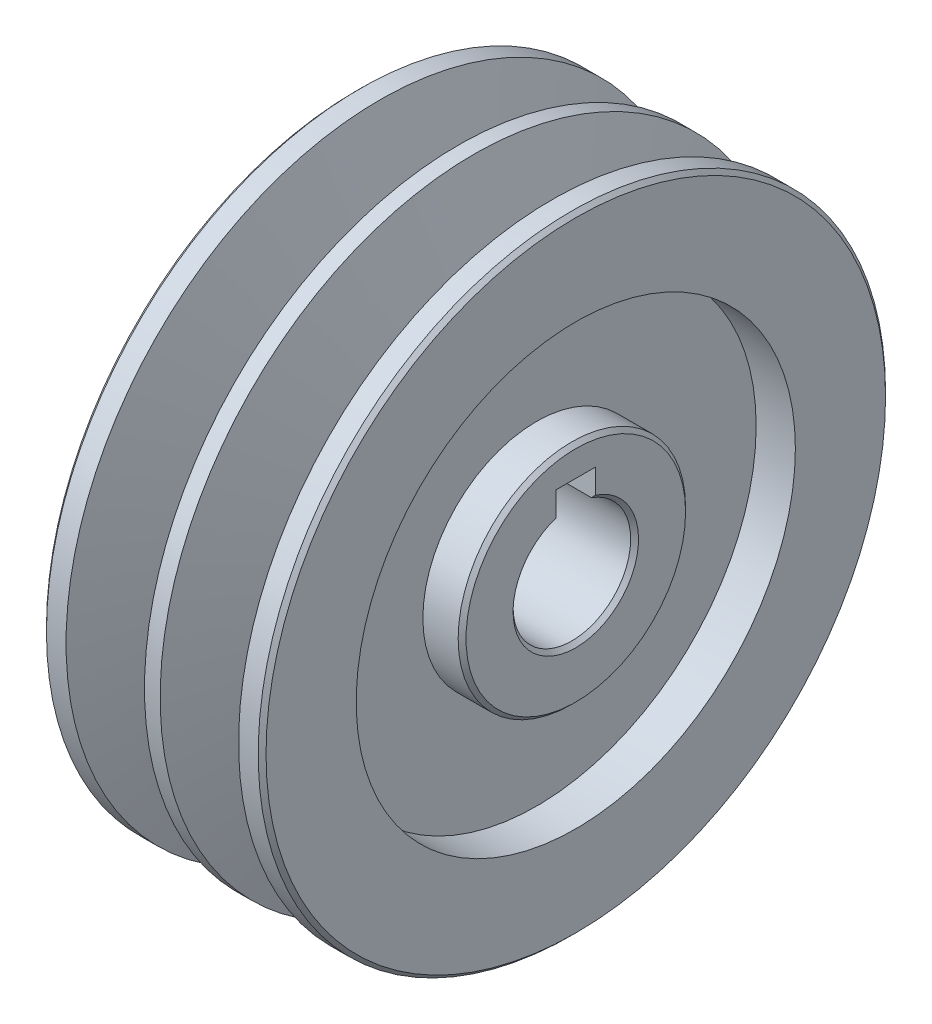
SolidWorks part; units mm, degrees
ref_plane "Front Plane" through (0, 0, 0) normal (0, 0, 1) x (1, 0, 0)
ref_plane "Top Plane" through (0, 0, 0) normal (0, 1, 0) x (1, 0, 0)
ref_plane "Right Plane" through (0, 0, 0) normal (1, 0, 0) x (0, 0, -1)
sketch "Sketch1" plane through (0, 0, 0) normal (0, 1, 0) x (1, 0, 0)
  line L0 (-14, 40) -> (-14, 28)
  line L1 (-14, 40) -> (-11, 40)
  line L2 (14, 40) -> (14, 28)
  line L3 (14, 28) -> (9, 28)
  line L4 (9, 28) -> (9, 14.5)
  line L5 (9, 14.5) -> (14, 14.5)
  line L6 (14, 14.5) -> (14, 7.5)
  line L7 (14, 7.5) -> (-14, 7.5)
  line L8 (-14, 7.5) -> (-14, 14.5)
  line L9 (-14, 14.5) -> (-9, 14.5)
  line L10 (-9, 14.5) -> (-9, 28)
  line L11 (-9, 28) -> (-14, 28)
  line L12 (0, 0) -> (0, 95.8906) construction
  line L13 (1, 40) -> (4.0573, 30)
  line L14 (4.0573, 30) -> (7.9427, 30)
  line L15 (7.9427, 30) -> (11, 40)
  line L16 (11, 40) -> (14, 40)
  line L17 (0, 0) -> (-42.3045, 0) construction
  line L18 (-11, 40) -> (-7.9427, 30)
  line L19 (-7.9427, 30) -> (-4.0573, 30)
  line L20 (-4.0573, 30) -> (-1, 40)
  line L21 (-1, 40) -> (1, 40)
  dimension "D1" = 10
  dimension "D2" = 10
  dimension "D3" = 34
  dimension "D4" = 28
  dimension "D5" = 28
  dimension "D6" = 5
  dimension "D7" = 7
  dimension "D8" = 7.5
  dimension "D9" = 40
  dimension "D10" = 12
  dimension "D11" = 10
  dimension "D12" = 34
  dimension "D13" = 34
  dimension "D14" = 2
revolve "Revolve1" add sketch "Sketch1" angle 360 about L17
chamfer "Chamfer1" distance 0.5 angle 45 3 edges at (14, 0, -7.5) (14, 0, -14.5) (14, 0, -40)
chamfer "Chamfer2" distance 0.5 angle 45 4 edges at (-14, 0, -14.5) (-14, 0, -7.5) (-14, 0, -40) (-14, 0, -28)
fillet "Fillet2" radius 1 2 edges at (-9, 0, -28) (-9, 0, -14.5)
sketch "Sketch2" plane through (14, 0, 0) normal (1, 0, 0) x (0, 0, -1)
  line L0 (-2.5, 7.5) -> (-2.5, 5.833)
  line L1 (-2.5, 10.7) -> (2.5, 10.7)
  line L2 (-2.5, 10.7) -> (-2.5, 7.5)
  line L4 (2.5, 10.7) -> (2.5, 7.5)
  line L5 (-2.5, 10.7) -> (2.5, 7.5) construction
  line L6 (-2.5, 7.5) -> (2.5, 10.7) construction
  line L7 (-2.5, 5.833) -> (2.5, 5.833)
  line L8 (2.5, 5.833) -> (2.5, 7.5)
  point P0 (0, 9.1)
  point P5 (0, 5.833)
  dimension "D1" = 3.2
  dimension "D2" = 5
  dimension "D3" = 10.7
extrude "Cut-Extrude1" cut sketch "Sketch2" against normal through all
